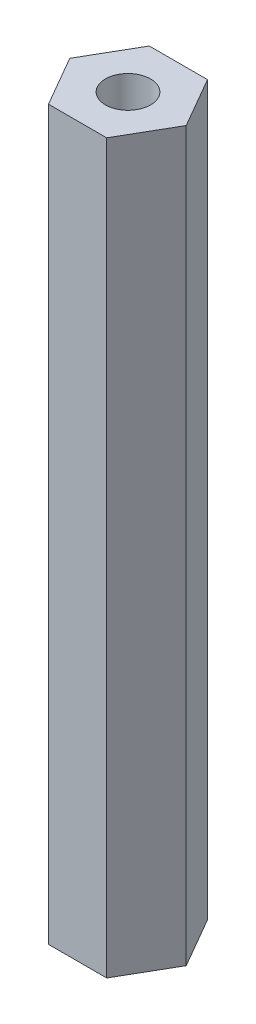
SolidWorks part; units mm, degrees
ref_plane "前基準面" through (0, 0, 0) normal (0, 0, 1) x (1, 0, 0)
ref_plane "上基準面" through (0, 0, 0) normal (0, 1, 0) x (1, 0, 0)
ref_plane "右基準面" through (0, 0, 0) normal (1, 0, 0) x (0, 0, -1)
sketch "草圖1" plane through (0, 0, 0) normal (0, 1, 0) x (1, 0, 0)
  line L1 (2, 3.4641) -> (-2, 3.4641)
  line L2 (-2, 3.4641) -> (-4, 0)
  line L3 (-4, 0) -> (-2, -3.4641)
  line L4 (-2, -3.4641) -> (2, -3.4641)
  line L5 (2, -3.4641) -> (4, 0)
  line L6 (4, 0) -> (2, 3.4641)
  circle A0 centre (0, 0) radius 3.4641 construction
  circle A1 centre (0, 0) radius 1.55
  dimension "D1" = 3.1
  dimension "D2" = 4
extrude "填料-伸長1" add sketch "草圖1" along normal blind 50 contours A1 | L1 L2 L3 L4 L5 L6
